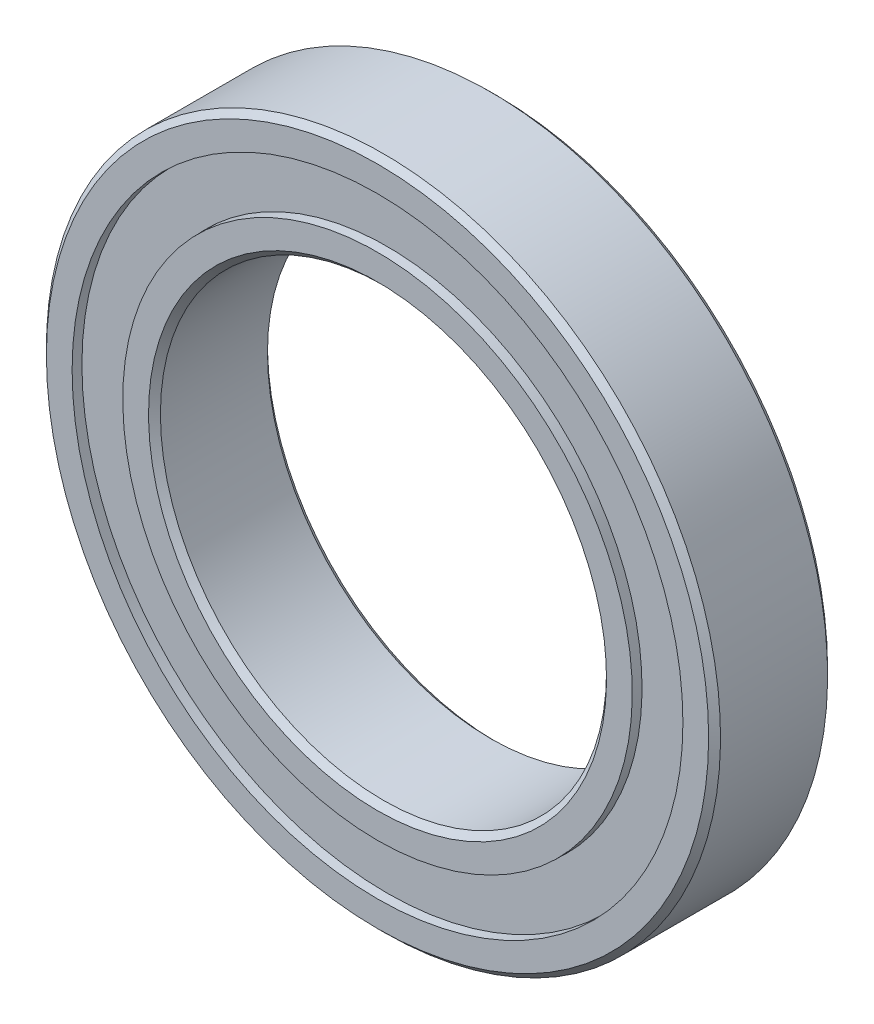
SolidWorks part; units mm, degrees
ref_plane "Front Plane" through (0, 0, 0) normal (0, 0, 1) x (1, 0, 0)
ref_plane "Top Plane" through (0, 0, 0) normal (0, 1, 0) x (1, 0, 0)
ref_plane "Right Plane" through (0, 0, 0) normal (1, 0, 0) x (0, 0, -1)
sketch "Sketch1" plane through (0, 0, 0) normal (0, 0, 1) x (1, 0, 0)
  circle A0 centre (0, 0) radius 34
  circle A1 centre (0, 0) radius 22.5
  dimension "OD" = 68
  dimension "ID" = 45
  dimension "For Shaft Diameter" = 45
  dimension "For Housing ID" = 68
sketch "Sketch8" plane through (0, 0, 0) normal (1, 0, 0) x (0, 0, -1)
  line L1 (-6, 34) -> (6, 34)
  line L2 (-6, 34) -> (-6, -34)
  line L3 (-6, -34) -> (6, -34)
  line L4 (6, 34) -> (6, -34)
  line L5 (-6, 34) -> (6, -34) construction
  line L6 (-6, -34) -> (6, 34) construction
  point P0 (0, 0)
  point P6 (0, -34)
  dimension "Width" = 12
sketch "Sketch5" plane through (0, 0, 0) normal (1, 0, 0) x (0, 0, -1)
  line L0 (-6, 0) -> (6, 0) construction
  line L1 (0, 34) -> (0, -34) construction
  line L2 (5.4, 34) -> (-5.4, 34)
  line L3 (-5.4, 34) -> (-6, 33.4)
  line L4 (-6, 33.4) -> (-6, 30.8056)
  line L5 (-6, 30.8056) -> (-2.6667, 30.8056)
  line L6 (6, 30.8056) -> (2.6667, 30.8056)
  line L7 (6, 33.4) -> (6, 30.8056)
  line L8 (5.4, 34) -> (6, 33.4)
  line L9 (0, 34) -> (0, 28.25) construction
  line L10 (0, 28.25) -> (0, 22.5) construction
  line L11 (-3.6935, 28.25) -> (-6, 28.25) construction
  line L12 (4.6563, 25.7198) -> (5.0373, 25.7198)
  line L13 (-4.6563, 25.7198) -> (-5.0373, 25.7198)
  line L14 (-4.6563, 25.7198) -> (-4.6563, 30.7802)
  line L15 (-4.6563, 30.7802) -> (-5.0373, 30.7802)
  line L16 (-5.0373, 25.7198) -> (-5.0373, 30.7802)
  line L17 (-4.6563, 25.7198) -> (-5.0373, 30.7802) construction
  line L18 (-4.6563, 30.7802) -> (-5.0373, 25.7198) construction
  line L19 (5.0373, 25.7198) -> (5.0373, 30.7802)
  line L20 (4.6563, 30.7802) -> (5.0373, 30.7802)
  line L21 (4.6563, 25.7198) -> (4.6563, 30.7802)
  line L22 (0, 34) -> (0, -34) construction
  line L23 (6, 0) -> (6, 34) construction
  line L24 (6, 34) -> (5.4, 34) construction
  line L25 (-6, 0) -> (-6, 34) construction
  line L26 (-6, 34) -> (-5.4, 34) construction
  line L27 (6, 0) -> (6, -34) construction
  line L28 (-6, 0) -> (-6, -34) construction
  line L29 (-6, -34) -> (6, -34) construction
  arc A0 (-2.6667, 30.8056) -> (2.6667, 30.8056) centre (0, 28.25) cw
  circle A1 centre (0, 28.25) radius 3.6935 construction
  point P14 (0, 22.5)
  point P15 (-4.8468, 28.25)
  dimension "D1" = 45
  dimension "D2" = 0.6
  dimension "D3" = 5.3333
  dimension "D4" = 2.5556
  dimension "D5" = 0.381
  dimension "D6" = 0.0254
revolve "Revolve1" add sketch "Sketch5" angle 360 about L0
sketch "Sketch3" plane through (0, 0, 0) normal (1, 0, 0) x (0, 0, -1)
  line L0 (-6, 25.6944) -> (-2.6667, 25.6944)
  line L1 (0, 34) -> (0, -34) construction
  line L2 (-6, 33.4) -> (-6, 30.8056) construction
  line L3 (-6, 25.6944) -> (-6, 23.1)
  line L4 (-5.4, 34) -> (-6, 33.4) construction
  line L5 (-6, 23.1) -> (-5.4, 22.5)
  line L6 (-5.4, 22.5) -> (5.4, 22.5)
  line L7 (5.4, 34) -> (5.4, -34) construction
  line L8 (5.4, 22.5) -> (6, 23.1)
  line L9 (6, -33.4) -> (6, 33.4) construction
  line L10 (6, 23.1) -> (6, 25.6944)
  line L11 (6, 25.6944) -> (2.6667, 25.6944)
  line L13 (5.4, 34) -> (6, 33.4) construction
  arc A0 (2.6667, 30.8056) -> (-2.6667, 30.8056) centre (0, 28.25) ccw construction
  arc A1 (2.6667, 25.6944) -> (-2.6667, 25.6944) centre (0, 28.25) cw
revolve "Revolve3" add sketch "Sketch3" angle 360 about L0
sketch "Sketch4" plane through (0, 0, 0) normal (1, 0, 0) x (0, 0, -1)
  line L0 (-3.6935, 28.25) -> (3.6935, 28.25)
  arc A2 (-3.6935, 28.25) -> (3.6935, 28.25) centre (0, 28.25) cw
  arc A3 (2.6667, 30.8056) -> (-2.6667, 30.8056) centre (0, 28.25) ccw construction
revolve "Revolve4" add sketch "Sketch4" angle 360 about L0
pattern_circular "CirPattern1" count 15 every 24 about axis through (0, 0, 0) along (0, 0, 1) of bodies 104
equation "\"D2@Sketch5\" = \"Width@Sketch8\" * .05"
equation "\"D3@Sketch5\" = \"Width@Sketch8\" / 2.25"
equation "\"D4@Sketch5\"=((\"OD@Sketch1\"-\"ID@Sketch1\")/2)/4.5"
equation "\"D2@CirPattern1\" = 360/\"Balls@CirPattern1\""
